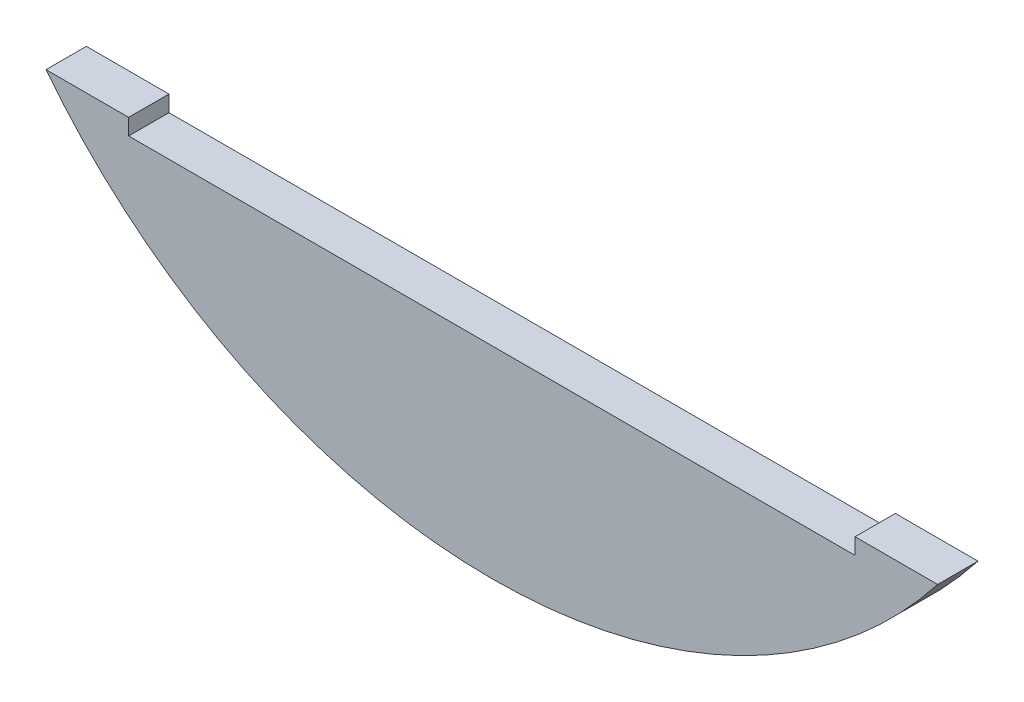
SolidWorks part; units mm, degrees
material "Balsa"
ref_plane "Plan de face" through (0, 0, 0) normal (0, 0, 1) x (1, 0, 0)
ref_plane "Plan de dessus" through (0, 0, 0) normal (0, 1, 0) x (1, 0, 0)
ref_plane "Plan de droite" through (0, 0, 0) normal (1, 0, 0) x (0, 0, -1)
sketch "Esquisse1" plane through (0, 0, 0) normal (0, 0, 1) x (1, 0, 0)
  line L0 (45, 45) -> (45, -45)
  line L1 (45, -45) -> (-45, -45)
  line L2 (-45, -45) -> (-45, 45)
  line L3 (-45, 45) -> (45, 45)
  line L8 (45, -45) -> (-45, 45) construction
  line L9 (-45, -45) -> (45, 45) construction
  circle A0 centre (0, 0) radius 175
  dimension "D2" = 350
  dimension "D3" = 90
  dimension "D1" = 90
extrude "Boss.-Extru.1" add sketch "Esquisse1" along normal blind 5
sketch "Esquisse2" plane through (0, 0, 5) normal (0, 0, 1) x (1, 0, 0)
  line L0 (-90, 0) -> (-49.5717, 0) construction
  line L1 (-156.4682, 78.3754) -> (-90, 40)
  line L2 (0, 0) -> (0, 175) construction
  line L3 (-90, 40) -> (-90, -40)
  line L4 (-90, -40) -> (-156.4682, -78.3754)
  circle A0 centre (0, 0) radius 175 construction
  arc A1 (-156.4682, 78.3754) -> (-156.4682, -78.3754) centre (0, 0) ccw
  dimension "D2" = 80
  dimension "D1" = 90
  dimension "D3" = 90
  dimension "D4" = 120
extrude "Enlèv. mat.-Extru.1" cut sketch "Esquisse2" against normal blind 10
sketch "Esquisse3" plane through (0, 0, 5) normal (0, 0, 1) x (1, 0, 0)
  line L1 (-200, 207) -> (200, 207)
  line L2 (-200, 207) -> (-200, -43)
  line L3 (-200, -43) -> (-95.1962, -43)
  line L4 (200, 207) -> (200, -43)
  line L6 (-45, -45) -> (45, -45) construction
  line L8 (-156.4682, -78.3754) -> (-90, -40) construction
  line L9 (-156.4682, -78.3754) -> (-95.1962, -43)
  line L10 (-55.2359, -43) -> (55.2359, -43)
  line L11 (169.6349, -43) -> (200, -43)
  arc A0 (-55.2359, -43) -> (55.2359, -43) centre (0, 0) ccw
  arc A1 (169.6349, -43) -> (-156.4682, -78.3754) centre (0, 0) cw
  arc A2 (-156.4682, -78.3754) -> (-156.4682, 78.3754) centre (0, 0) ccw construction
  dimension "D5" = 70
  dimension "D1" = 400
  dimension "D2" = 200
  dimension "D3" = 250
  dimension "D4" = 2
extrude "Enlèv. mat.-Extru.4" cut sketch "Esquisse3" against normal blind 10
